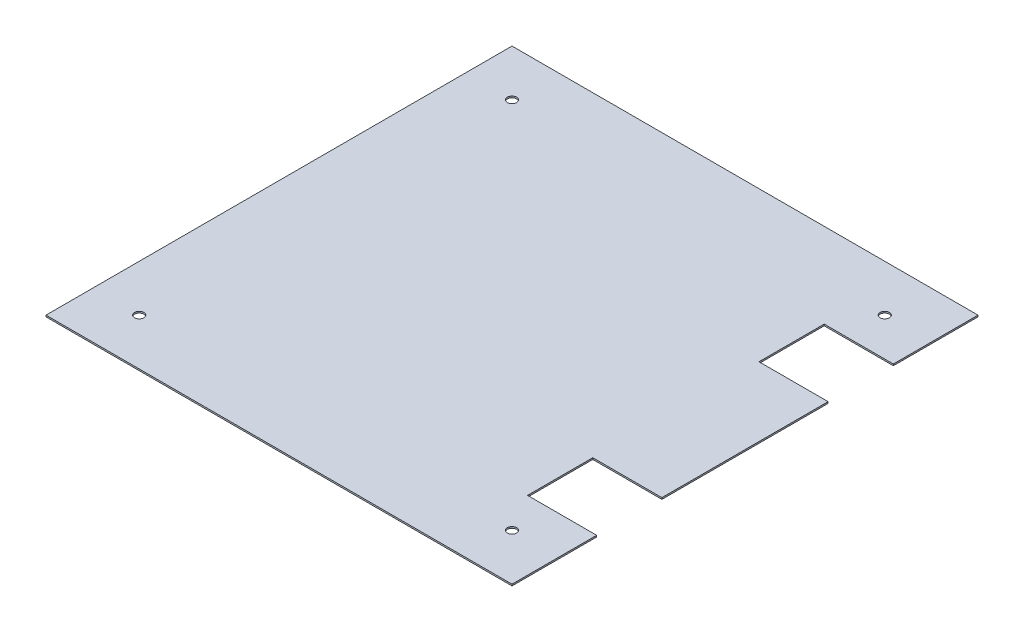
SolidWorks part; units mm, degrees
ref_plane "前视基准面" through (0, 0, 0) normal (0, 0, 1) x (1, 0, 0)
ref_plane "上视基准面" through (0, 0, 0) normal (0, 1, 0) x (1, 0, 0)
ref_plane "右视基准面" through (0, 0, 0) normal (1, 0, 0) x (0, 0, -1)
sketch "草图1" plane through (0, 0, 0) normal (0, 1, 0) x (1, 0, 0)
  line L1 (-56.7569, 16.2855) -> (243.2431, 16.2855)
  line L2 (-56.7569, 16.2855) -> (-56.7569, -283.7145)
  line L3 (-56.7569, -283.7145) -> (243.2431, -283.7145)
  line L4 (243.2431, 16.2855) -> (243.2431, -283.7145)
  dimension "D1" = 300
  dimension "D2" = 300
extrude "凸台-拉伸1" add sketch "草图1" along normal blind 1
sketch "草图2" plane through (0, 0, 0) normal (0, 1, 0) x (1, 0, 0)
  line L0 (243.2431, 16.2855) -> (-56.7569, 16.2855) construction
  line L1 (-56.7569, 16.2855) -> (-56.7569, -283.7145) construction
  line L2 (243.2431, -283.7145) -> (243.2431, 16.2855) construction
  line L3 (-56.7569, -283.7145) -> (243.2431, -283.7145) construction
  circle A0 centre (-26.7569, -13.7145) radius 3
  circle A1 centre (213.2431, -13.7145) radius 3
  circle A2 centre (213.2431, -253.7145) radius 3
  circle A3 centre (-26.7569, -253.7145) radius 3
  dimension "D1" = 30
  dimension "D3" = 30
  dimension "D4" = 30
  dimension "D2" = 30
extrude "切除-拉伸2" cut sketch "草图2" along normal through all
sketch "草图3" plane through (0, 0, 0) normal (0, 1, 0) x (1, 0, 0)
  line L1 (-56.7569, -283.7145) -> (243.2431, -283.7145) construction
  line L2 (198.7431, -187.2145) -> (243.2431, -187.2145)
  line L3 (198.7431, -187.2145) -> (198.7431, -229.2145)
  line L4 (198.7431, -229.2145) -> (243.2431, -229.2145)
  line L5 (243.2431, -283.7145) -> (243.2431, 16.2855) construction
  line L6 (243.2431, 16.2855) -> (-56.7569, 16.2855) construction
  line L7 (198.7431, -38.2145) -> (243.2431, -38.2145)
  line L8 (198.7431, -38.2145) -> (198.7431, -80.2145)
  line L9 (198.7431, -80.2145) -> (243.2431, -80.2145)
  line L10 (243.2431, -38.2145) -> (243.2431, -80.2145)
  line L11 (243.2431, -187.2145) -> (243.2431, -229.2145)
  dimension "D1" = 42
  dimension "D2" = 44.5
  dimension "D3" = 54.5
  dimension "D4" = 42
  dimension "D5" = 54.5
  dimension "D6" = 44.5
extrude "切除-拉伸4" cut sketch "草图3" along normal through all
